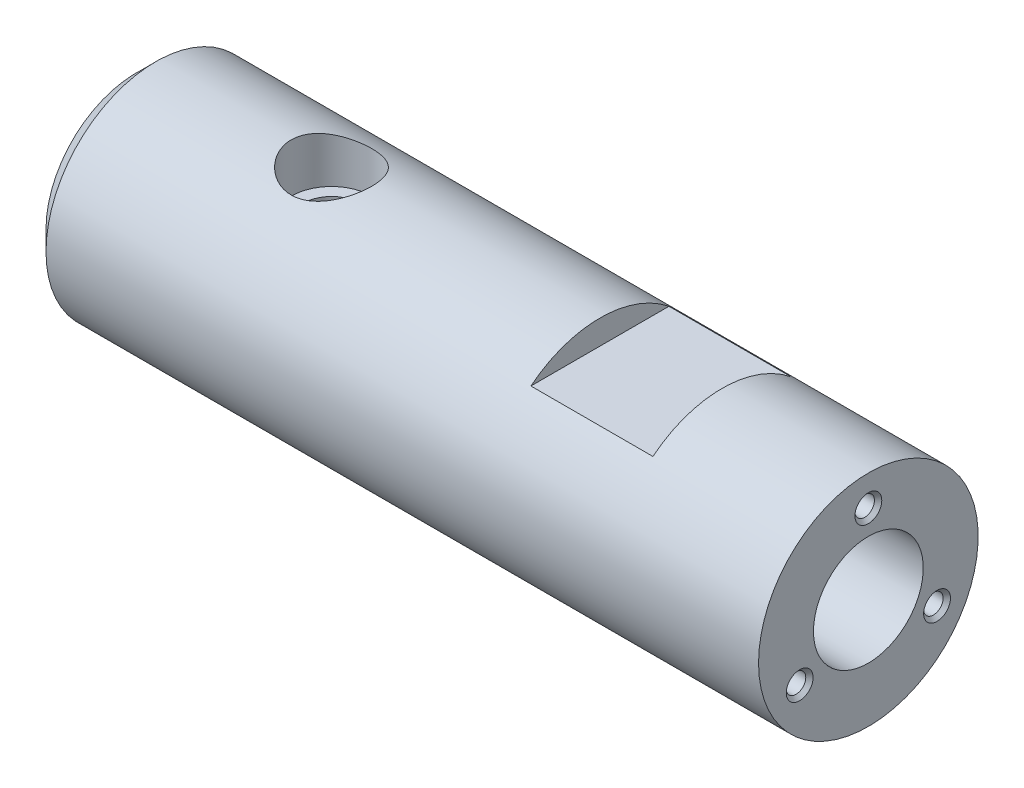
SolidWorks part; units mm, degrees
ref_plane "Спереди" through (0, 0, 0) normal (0, 0, 1) x (1, 0, 0)
ref_plane "Сверху" through (0, 0, 0) normal (0, 1, 0) x (1, 0, 0)
ref_plane "Справа" through (0, 0, 0) normal (1, 0, 0) x (0, 0, -1)
ref_axis "Ось1" through (-41.0409, 0, 0) along (1, 0, 0)
sketch "Эскиз1" plane through (0, 0, 0) normal (0, 0, 1) x (1, 0, 0)
  line L0 (-16, 0) -> (0, 0) construction
  line L1 (-16, 2.55) -> (-16, 4.75)
  line L2 (-16, 4.75) -> (-14.6, 4.75)
  line L3 (-14.6, 4.75) -> (-14.6, 6.75)
  line L4 (-14.6, 6.75) -> (-16, 6.75)
  line L5 (-16, 6.75) -> (-16, 7.4)
  line L6 (-14.4, 9) -> (44, 9)
  line L7 (44, 9) -> (44, 4.5)
  line L8 (-13, 2.55) -> (-16, 2.55)
  line L9 (-13, 2.55) -> (-13, 4.5)
  line L10 (-13, 4.5) -> (44, 4.5)
  line L11 (0, 0) -> (0, 9.4642) construction
  line L12 (44, 6.5) -> (35.6458, 6.5) construction
  line L13 (3.3, 9) -> (3.3, 5) construction
  line L14 (3.3, 5) -> (2.3, 5) construction
  line L15 (2.3, 5) -> (2.3, 0) construction
  line L16 (2.3, 0) -> (0, 0) construction
  line L17 (22, 9) -> (22, 7) construction
  line L18 (22, 7) -> (32, 7) construction
  line L19 (32, 7) -> (32, 9) construction
  line L20 (-16, 7.4) -> (-14.4, 9)
  point P9 (-16, 9)
  point P18 (-13, 3.525)
  dimension "D1" = 5.1
  dimension "D2" = 9.5
  dimension "D3" = 18
  dimension "D4" = 13.5
  dimension "D5" = 60
  dimension "D6" = 9
  dimension "D7" = 16
  dimension "D8" = 1.4
  dimension "D9" = 57
  dimension "D10" = 5
  dimension "D11" = 6.6
  dimension "D12" = 4.6
  dimension "D13" = 13
  dimension "D14" = 14
  dimension "D15" = 12
  dimension "D16" = 10
  dimension "D17" = 45
revolve "Повернуть1" add sketch "Эскиз1" angle 360 about L0
cosmetic thread "Условное изображение резьбы1" parameters "D1"=8, "D2"=16.344
sketch "Эскиз2" plane through (0, 0, 0) normal (0, 0, 1) x (1, 0, 0)
  line L0 (0, 0) -> (0, 9.4642) construction
  line L1 (2.3, 0) -> (0, 0) construction
  line L2 (2.3, 5) -> (2.3, 0) construction
  line L3 (3.3, 5) -> (2.3, 5) construction
  line L4 (3.3, 9) -> (3.3, 5) construction
  line L5 (-14.4, 9) -> (44, 9) construction
  line L6 (0, 0) -> (0, 9)
  line L7 (2.3, 0) -> (0, 0)
  line L8 (2.3, 5) -> (2.3, 0)
  line L9 (3.3, 5) -> (2.3, 5)
  line L10 (3.3, 9) -> (3.3, 5)
  line L11 (0, 9) -> (3.3, 9)
revolve "Вырез-Повернуть1" cut sketch "Эскиз2" angle 360 about L6
sketch "Эскиз3" plane through (0, 0, 0) normal (0, 0, 1) x (1, 0, 0)
  line L0 (32, 7) -> (32, 9) construction
  line L1 (22, 9) -> (22, 7) construction
  line L2 (-14.4, 9) -> (44, 9) construction
  line L3 (22, 7) -> (32, 7) construction
  line L4 (22, 7) -> (32, 7)
  line L5 (22, 9) -> (22, 7)
  line L6 (32, 7) -> (32, 9)
  line L7 (22, 9) -> (32, 9)
extrude "Вырез-Вытянуть1" cut sketch "Эскиз3" against normal through all and the other way through all
hole_wizard "Отверстие обработанное метчиком M21" positions "Эскиз4" profile "Эскиз5" tap size "M2" standard "ISO"
sketch "Эскиз4" plane through (44, 0, 0) normal (1, 0, 0) x (0, 0, -1)
  point P0 (0, 6.5)
sketch "Эскиз5" plane through (44, 6.5, 0) normal (0, 1, 0) x (0, 0, -1)
  line L0 (0, 0) -> (0, 8.4807)
  line L1 (0, 8.4807) -> (0.8, 8)
  line L2 (0.8, 8) -> (0.8, 0.3)
  line L3 (0.8, 0.3) -> (1.1, 0)
  line L5 (1.1, 0) -> (0, 0)
  line L6 (-0.8, 0.3) -> (-1.1, 0) construction
  line L10 (0, 8.4807) -> (-0.8, 8) construction
  line L11 (0, -6.35) -> (0, 107.95) construction
  dimension "Диаметр сверла" = 1.6
  dimension "Глубина сверла" = 8
  dimension "Диаметр передней зенковки" = 2.2
  dimension "Угол передней зенковки" = 90
  dimension "Угол заточки сверла" = 118
cosmetic thread "Отверстие резьбы1" parameters "D1"=5, "D2"=2
pattern_circular "Круговой массив1" count 2 over 360 about axis through (-41.0409, 0, 0) along (1, 0, 0) of "Вырез-Вытянуть1"
pattern_circular "Круговой массив2" count 3 over 360 about axis through (0, 0, 0) along (1, 0, 0) of "Отверстие обработанное метчиком M21"
